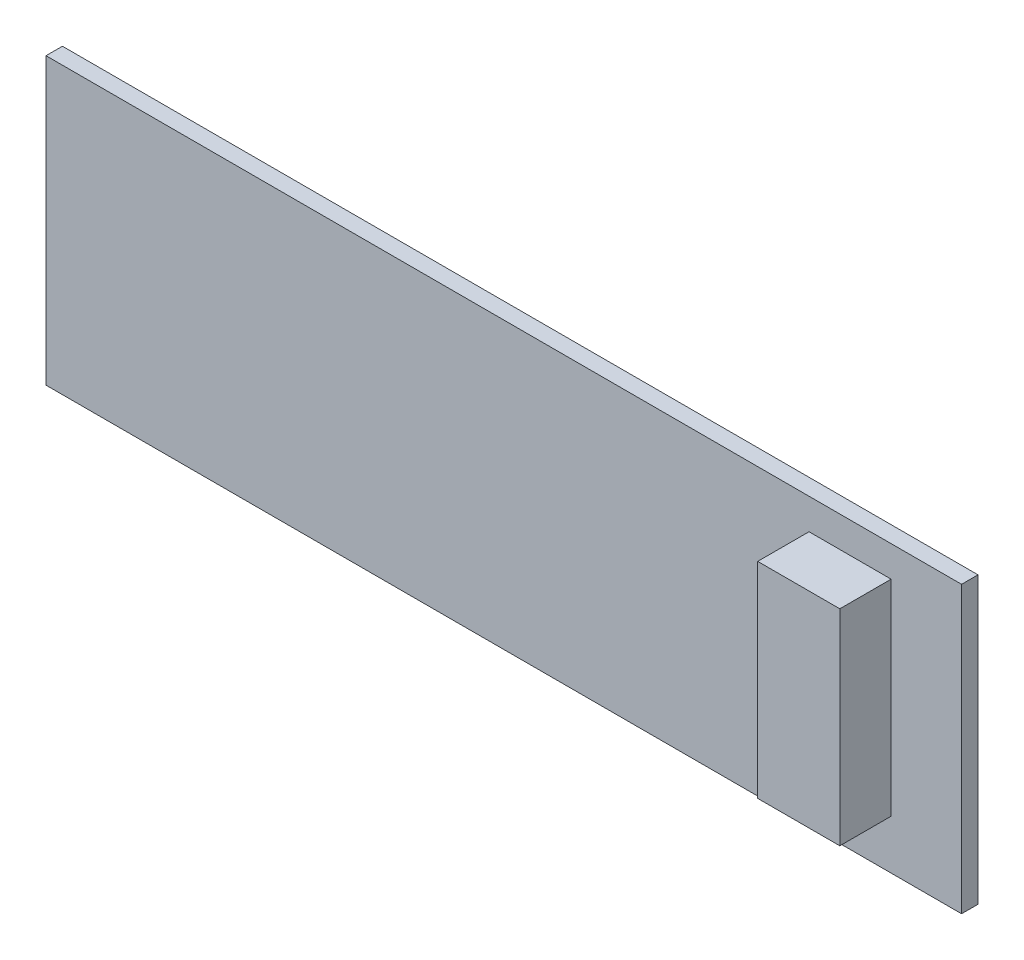
SolidWorks part; units mm, degrees
ref_plane "Front Plane" through (0, 0, 0) normal (0, 0, 1) x (1, 0, 0)
ref_plane "Top Plane" through (0, 0, 0) normal (0, 1, 0) x (1, 0, 0)
ref_plane "Right Plane" through (0, 0, 0) normal (1, 0, 0) x (0, 0, -1)
sketch "Sketch1" plane through (0, 0, 0) normal (0, 0, 1) x (1, 0, 0)
  line L0 (-44.6, -13.9) -> (44.6, -13.9)
  line L1 (44.6, -13.9) -> (44.6, 13.9)
  line L2 (44.6, 13.9) -> (-44.6, 13.9)
  line L3 (-44.6, 13.9) -> (-44.6, -13.9)
extrude "Boss-Extrude1" add sketch "Sketch1" against normal blind 1.6
sketch "Sketch2" plane through (0, 0, 0) normal (0, 0, 1) x (1, 0, 0)
  line L0 (37.7376, -9.0968) -> (29.7376, -9.0968)
  line L1 (29.7376, -9.0968) -> (29.7376, 10.9032)
  line L2 (29.7376, 10.9032) -> (37.7376, 10.9032)
  line L3 (37.7376, 10.9032) -> (37.7376, -9.0968)
extrude "Boss-Extrude2" add sketch "Sketch2" along normal blind 5
